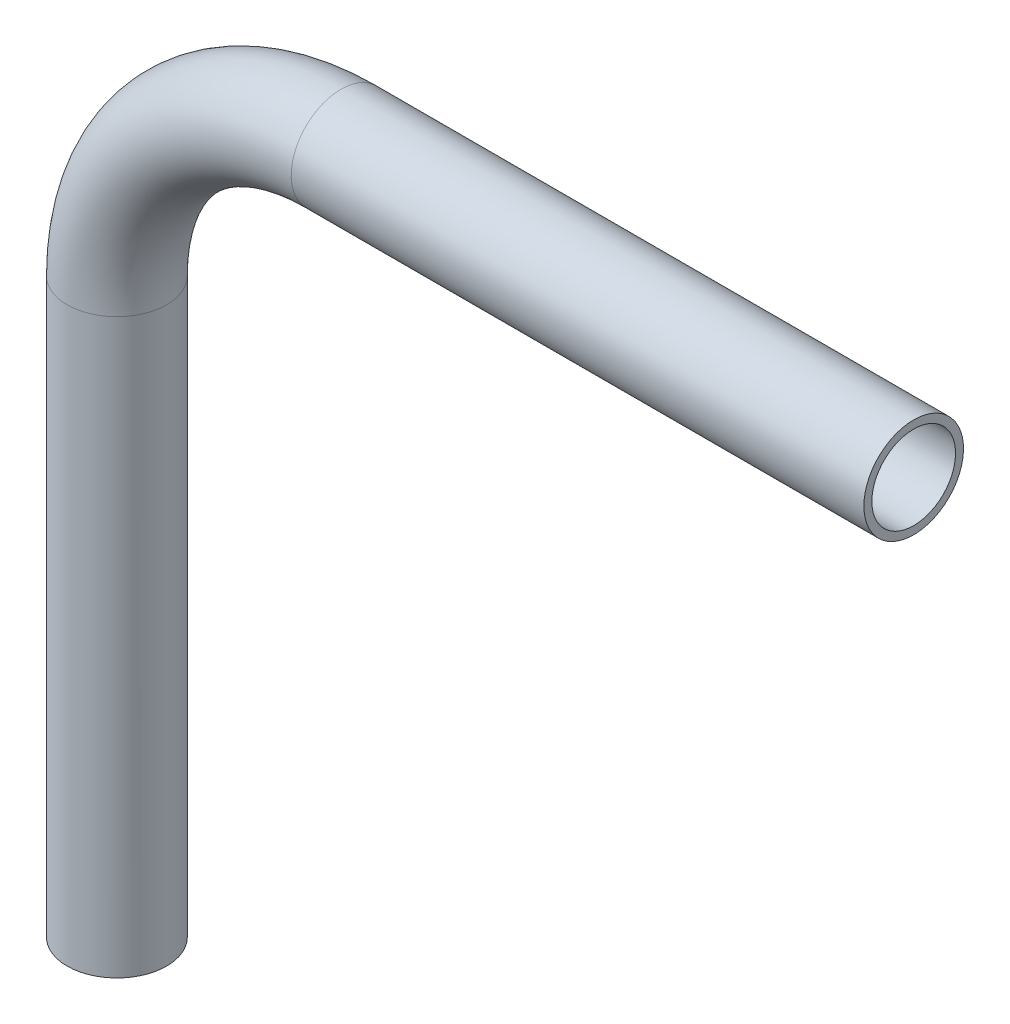
SolidWorks part; units mm, degrees
ref_plane "Front Plane" through (0, 0, 0) normal (0, 0, 1) x (1, 0, 0)
ref_plane "Top Plane" through (0, 0, 0) normal (0, 1, 0) x (1, 0, 0)
ref_plane "Right Plane" through (0, 0, 0) normal (1, 0, 0) x (0, 0, -1)
sketch "Sketch1" plane through (0, 0, 0) normal (0, 0, 1) x (1, 0, 0)
  line L0 (0, 0) -> (0, 36.5125)
  line L1 (14.2875, 50.8) -> (50.8, 50.8)
  line L2 (3.4925, 0) -> (-3.4925, 0) construction
  arc A0 (14.2875, 50.8) -> (0, 36.5125) centre (14.2875, 36.5125) ccw
  dimension "D1" = 14.2875
  dimension "D2" = 50.8
  dimension "D3" = 50.8
sketch "Sketch2" plane through (0, 0, 0) normal (0, 1, 0) x (1, 0, 0)
  circle A0 centre (0, 0) radius 3.175
  circle A1 centre (0, 0) radius 2.667
  dimension "D1" = 6.35
  dimension "D2" = 5.334
sweep "Sweep1" add profiles "Sketch2" path "Sketch1"
